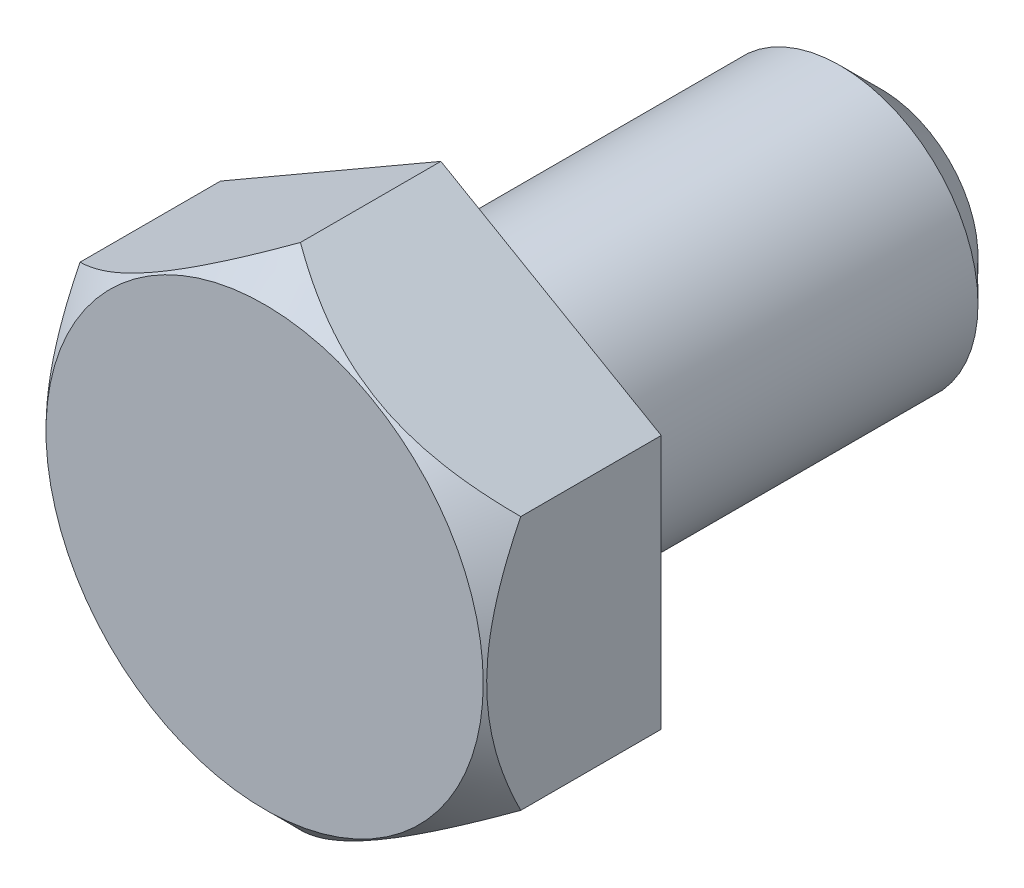
SolidWorks part; units mm, degrees
ref_plane "Спереди" through (0, 0, 0) normal (0, 0, 1) x (1, 0, 0)
ref_plane "Сверху" through (0, 0, 0) normal (0, 1, 0) x (1, 0, 0)
ref_plane "Справа" through (0, 0, 0) normal (1, 0, 0) x (0, 0, -1)
sketch "Эскиз1" plane through (0, 0, 0) normal (0, 0, 1) x (1, 0, 0)
  line L0 (0, 4.93) -> (0, -5.4719) construction
  line L1 (-5.0323, 0) -> (5.1026, 0) construction
  line L3 (0, 9.2376) -> (-8, 4.6188)
  line L4 (-8, 4.6188) -> (-8, -4.6188)
  line L5 (-8, -4.6188) -> (0, -9.2376)
  line L6 (0, -9.2376) -> (8, -4.6188)
  line L7 (8, -4.6188) -> (8, 4.6188)
  line L8 (8, 4.6188) -> (0, 9.2376)
  circle A0 centre (0, 0) radius 8 construction
extrude "Вытянуть1" add sketch "Эскиз1" along normal blind 6.4
sketch "Эскиз2" plane through (0, 0, 0) normal (0, 0, -1) x (-1, 0, 0)
  circle A0 centre (0, 0) radius 5
extrude "Вытянуть2" add sketch "Эскиз2" along normal blind 16
ref_axis "Ось4" through (0, 0, -3.5347) along (0, 0, -1)
sketch "Эскиз15" plane through (0, 0, 0) normal (1, 0, 0) x (0, 0, -1)
  line L0 (-6.4, 9.2376) -> (-6.4, 7.9376)
  line L1 (-6.4, 4.6188) -> (-6.4, 9.2376) construction
  line L2 (-6.4, 7.9376) -> (-5.1, 9.2376)
  line L3 (-6.4, 9.2376) -> (0, 9.2376) construction
  line L4 (-5.1, 9.2376) -> (-6.4, 9.2376)
revolve "Вырез-Повернуть1" cut sketch "Эскиз15" angle 360 about axis through (0, 0, -3.5347) along (0, 0, -1)
ref_plane "Плоскость1" through (0, 0, 0) normal (0, -1, 0) x (1, 0, 0)
chamfer "Фаска1" distance 1.5 angle 45 1 edges at (-5, 0, -16)
